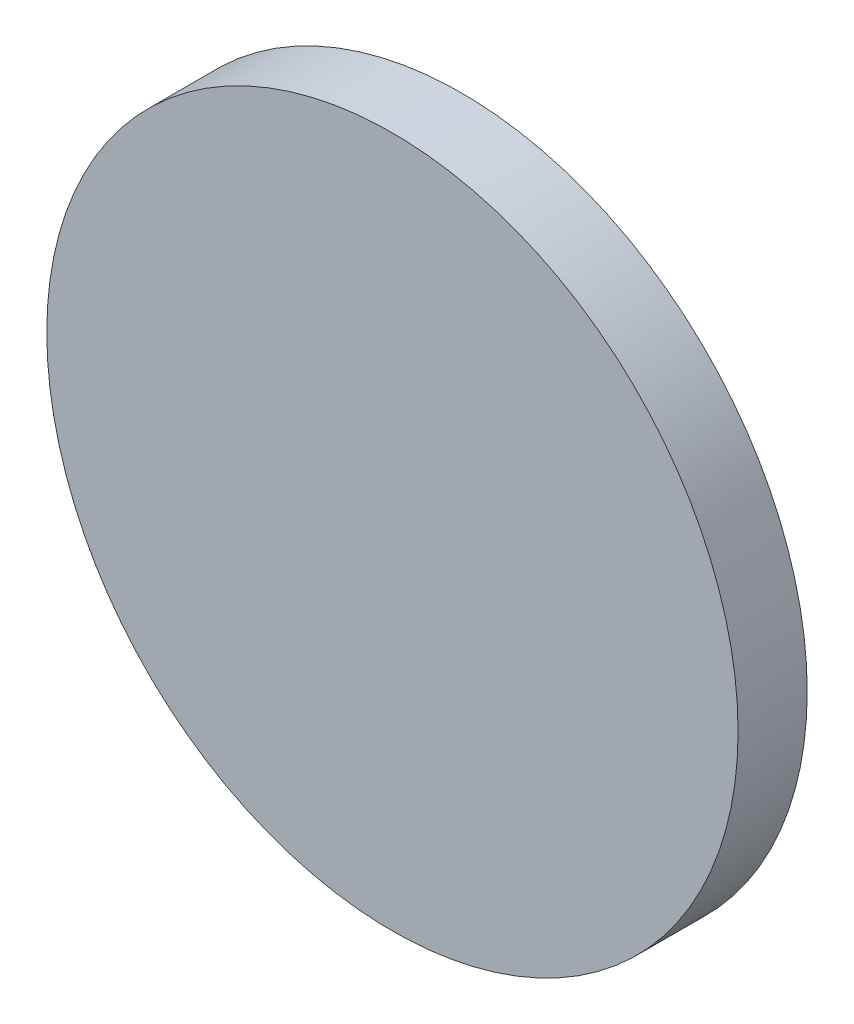
SolidWorks part; units mm, degrees
ref_plane "前视基准面" through (0, 0, 0) normal (0, 0, 1) x (1, 0, 0)
ref_plane "上视基准面" through (0, 0, 0) normal (0, 1, 0) x (1, 0, 0)
ref_plane "右视基准面" through (0, 0, 0) normal (1, 0, 0) x (0, 0, -1)
other "Configuration Table"
sketch "Sketch1" plane through (0, 0, 0) normal (0, 0, 1) x (1, 0, 0)
  circle A0 centre (0, 0) radius 50
extrude "Boss-Extrude1" add sketch "Sketch1" along normal blind 10
